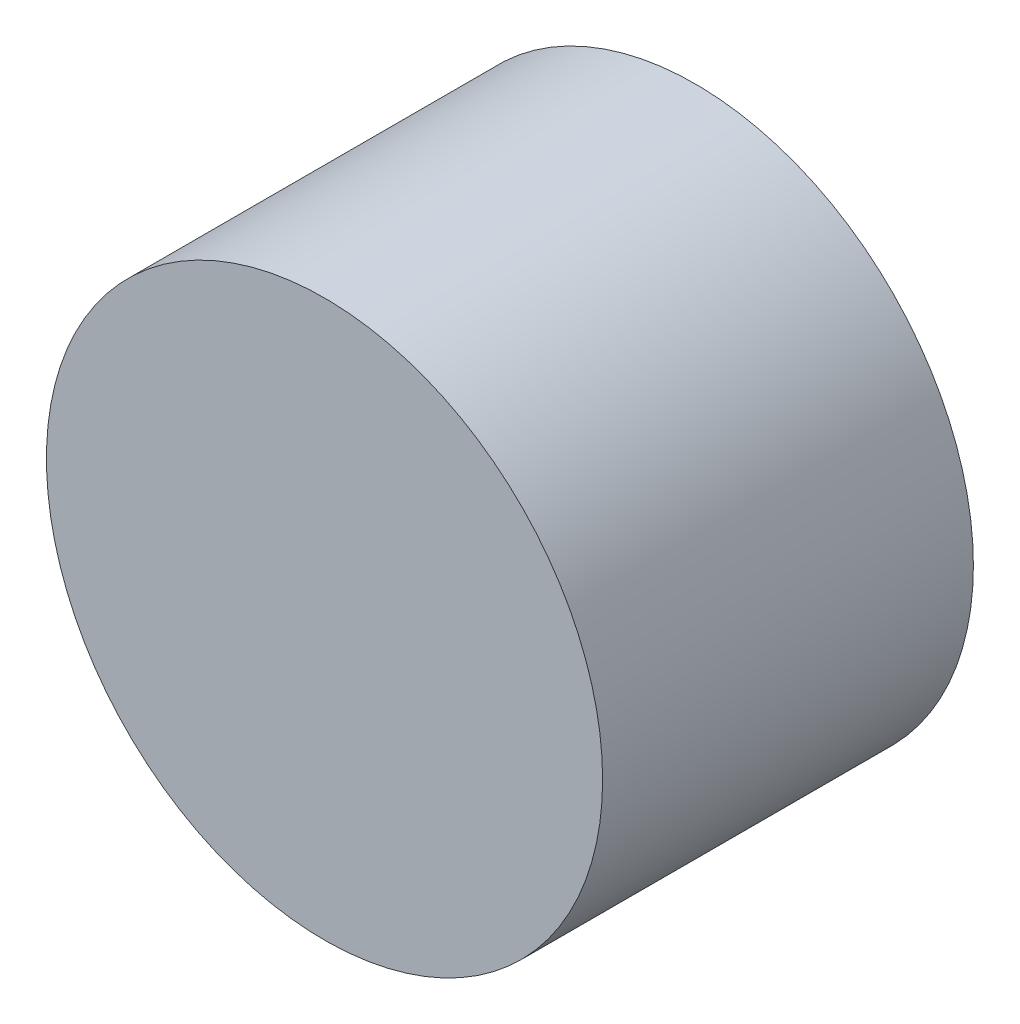
SolidWorks part; units mm, degrees
ref_plane "前视基准面" through (0, 0, 0) normal (0, 0, 1) x (1, 0, 0)
ref_plane "上视基准面" through (0, 0, 0) normal (0, 1, 0) x (1, 0, 0)
ref_plane "右视基准面" through (0, 0, 0) normal (1, 0, 0) x (0, 0, -1)
other "Configuration Table"
sketch "草图1" plane through (0, 0, 0) normal (0, 0, 1) x (1, 0, 0)
  circle A0 centre (0, 0) radius 18
extrude "凸台-拉伸1" add sketch "草图1" along normal blind 24
